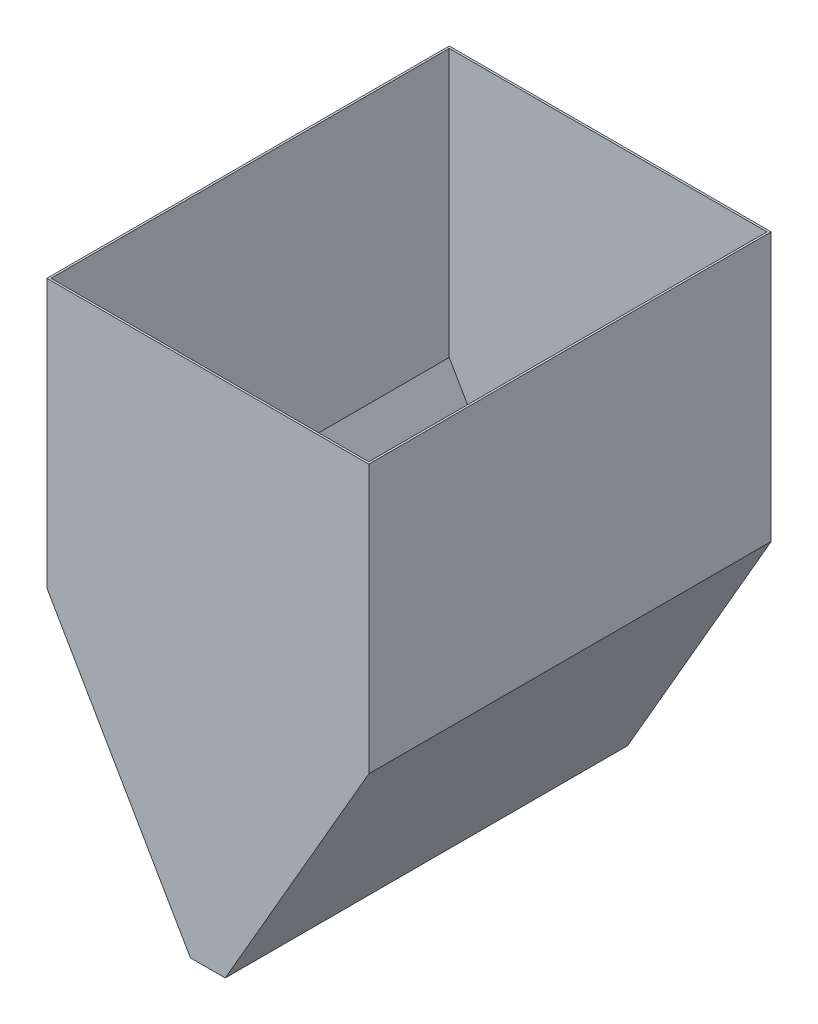
SolidWorks part; units mm, degrees
material "AISI 304"
ref_plane "Alzado" through (0, 0, 0) normal (0, 0, 1) x (1, 0, 0)
ref_plane "Planta" through (0, 0, 0) normal (0, 1, 0) x (1, 0, 0)
ref_plane "Vista lateral" through (0, 0, 0) normal (1, 0, 0) x (0, 0, -1)
sketch "Croquis1" plane through (0, 0, 0) normal (0, 1, 0) x (1, 0, 0)
  line L1 (-60, 75) -> (60, 75)
  line L2 (-60, 75) -> (-60, -75)
  line L3 (-60, -75) -> (60, -75)
  line L4 (60, 75) -> (60, -75)
  line L5 (-60, 75) -> (60, -75) construction
  line L6 (-60, -75) -> (60, 75) construction
  point P0 (0, 0)
  dimension "D1" = 120
  dimension "D2" = 150
ref_plane "Plano1" through (0, -92.664, 0) normal (0, 1, 0) x (1, 0, 0)
sketch "Croquis2" plane through (0, -92.664, 0) normal (0, 1, 0) x (1, 0, 0)
  line L1 (-6.5, 75) -> (6.5, 75)
  line L2 (-6.5, 75) -> (-6.5, -75)
  line L3 (-6.5, -75) -> (6.5, -75)
  line L4 (6.5, 75) -> (6.5, -75)
  line L5 (-6.5, 75) -> (6.5, -75) construction
  line L6 (-6.5, -75) -> (6.5, 75) construction
  line L7 (60, 75) -> (60, -75) construction
  point P0 (0, 0)
  dimension "D1" = 13
loft "Recubrir1" add profiles "Croquis1", "Croquis2"
sketch "Croquis3" plane through (0, 0, 0) normal (0, 1, 0) x (1, 0, 0)
  line L1 (-60, 75) -> (60, 75)
  line L2 (-60, 75) -> (-60, -75)
  line L3 (-60, -75) -> (60, -75)
  line L4 (60, 75) -> (60, -75)
extrude "Saliente-Extruir1" add sketch "Croquis3" along normal blind 100
shell "Vaciado2" thickness 0.76
